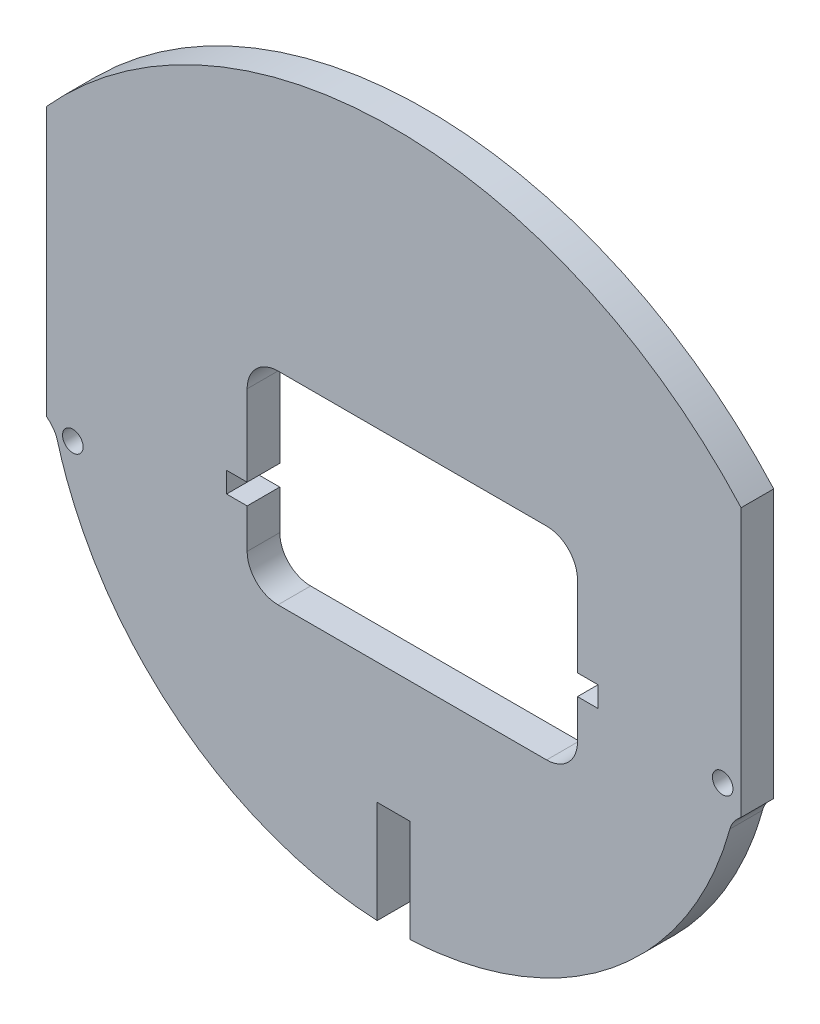
SolidWorks part; units mm, degrees
ref_plane "Front Plane" through (0, 0, 0) normal (0, 0, 1) x (1, 0, 0)
ref_plane "Top Plane" through (0, 0, 0) normal (0, 1, 0) x (1, 0, 0)
ref_plane "Right Plane" through (0, 0, 0) normal (1, 0, 0) x (0, 0, -1)
sketch "Sketch1" plane through (0, 0, 299.79) normal (0, 0, 1) x (1, 0, 0)
  line L4 (33.8, -7.3668) -> (33.8, 18.7258)
  line L5 (-33.8, 18.7232) -> (-33.8, -7.3668)
  line L6 (33.8, -7.3668) -> (33.8, 18.7258)
  line L7 (-33.8, 18.7232) -> (-33.8, -7.3668)
  arc A2 (33.8, 18.7258) -> (-33.8, 18.7232) centre (0.0012, -11.6296) ccw
  arc A3 (33.8, 18.7258) -> (-33.8, 18.7232) centre (0.0012, -11.6296) ccw
  spline S8 degree 3 poles (-1016.2927, 2781.193) (-581.3061, 1300.0591) (-161.7758, -90.3852) (11.2723, -31.8769) (11.7093, -31.7192) (12.5722, -31.3883) (13.8533, -30.8679) (16.7482, -29.4839) (19.0662, -28.003) (20.9048, -26.6015) (21.2687, -26.3121) (21.9818, -25.721) (22.3313, -25.4192) (23.3593, -24.4955) (25.3334, -22.5755) (27.0578, -20.4334) (28.6095, -18.1378) (29.099, -17.3449) (30.0051, -15.7345) (30.4243, -14.9144) (73.6573, 78.615) (-299.6884, 354.0447) (-2573.4248, 1463.866) knots -12.045008 -12.045008 -12.045008 -12.045008 0.25 0.25 0.28125 0.28125 0.3125 0.375 0.5 0.5 0.53125 0.53125 0.5625 0.5625 0.625 0.75 0.75 0.8125 0.8125 0.875 0.875 7.815594 7.815594 7.815594 7.815594 only from (0, -33.7996) to (32.7115, -8.8898)
  spline S9 degree 3 poles (3012.7008, -332.9993) (194.5659, -142.2921) (21.2536, -24.2042) (45.0624, 8.2078) (207.3281, -123.8641) (-2059.6696, 2140.7862) knots -30.844141 -30.844141 -30.844141 -30.844141 0.5 0.5 32.000269 32.000269 32.000269 32.000269 only from (32.7115, -8.8898) to (33.8, -7.3668)
  spline S10 degree 3 poles (1931.9323, 2258.2217) (-186.0941, -116.3959) (-47.7859, 6.5702) (-33.3262, -7.7914) (-33.2211, -7.9122) (-33.0345, -8.1665) (-32.9521, -8.3007) (-26.9906, -20.3777) (-108.782, -90.3547) (-1945.2248, 2299.9192) knots -31.496025 -31.496025 -31.496025 -31.496025 0.25 0.25 0.5 0.5 0.75 0.75 21.739069 21.739069 21.739069 21.739069 only from (-33.8, -7.3668) to (-32.7115, -8.8898)
  spline S11 degree 3 poles (2544.6593, 1514.4209) (266.9927, 341.713) (-71.9551, 75.0102) (-30.0469, -15.7324) (-29.1497, -17.3351) (-27.8537, -19.2568) (-27.5859, -19.6367) (-27.0375, -20.381) (-26.1942, -21.4772) (-25.2894, -22.5133) (-23.4001, -24.5077) (-22.0369, -25.736) (-20.1986, -27.1404) (-19.8234, -27.4151) (-18.307, -28.4773) (-17.131, -29.1958) (-14.2997, -30.6962) (-12.6159, -31.4206) (-9.9927, -32.3105) (-9.0996, -32.5737) (-7.3094, -33.0214) (-6.4087, -33.2074) (264.603, -77.6051) (1022.8864, 3211.8785) (666.5513, -1110.289) knots -6.570571 -6.570571 -6.570571 -6.570571 0.125 0.125 0.25 0.25 0.28125 0.28125 0.3125 0.375 0.375 0.5 0.5 0.53125 0.53125 0.625 0.625 0.75 0.75 0.8125 0.8125 0.875 0.875 19.504434 19.504434 19.504434 19.504434 only from (-32.7115, -8.8898) to (0, -33.7996)
  spline S12 degree 3 poles (0, -33.7996) (3.712, -33.7995) (7.3238, -33.2119) (11.2723, -31.8769) (11.7093, -31.7192) (12.5722, -31.3883) (13.8533, -30.8679) (16.7482, -29.4839) (19.0662, -28.003) (20.9048, -26.6015) (21.2687, -26.3121) (21.9818, -25.721) (22.3313, -25.4192) (23.3593, -24.4955) (25.3334, -22.5755) (27.0578, -20.4334) (28.6095, -18.1378) (29.099, -17.3449) (30.0051, -15.7345) (30.4243, -14.9144) (31.5818, -12.4103) (32.2185, -10.6815) (32.7115, -8.8898) knots 0 0 0 0 0.25 0.25 0.28125 0.28125 0.3125 0.375 0.5 0.5 0.53125 0.53125 0.5625 0.5625 0.625 0.75 0.75 0.8125 0.8125 0.875 0.875 1 1 1 1
  spline S13 degree 3 poles (32.7115, -8.8898) (32.7967, -8.5801) (32.939, -8.2963) (33.3179, -7.7806) (33.5452, -7.5601) (33.8, -7.3668) knots 0 0 0 0 0.5 0.5 1 1 1 1
  spline S14 degree 3 poles (-33.8, -7.3668) (-33.6728, -7.4633) (-33.5521, -7.567) (-33.3262, -7.7914) (-33.2211, -7.9122) (-33.0345, -8.1665) (-32.9521, -8.3007) (-32.8117, -8.585) (-32.754, -8.7354) (-32.7115, -8.8898) knots 0 0 0 0 0.25 0.25 0.5 0.5 0.75 0.75 1 1 1 1
  spline S15 degree 3 poles (-32.7115, -8.8898) (-32.2185, -10.6814) (-31.583, -12.4063) (-30.0469, -15.7324) (-29.1497, -17.3351) (-27.8537, -19.2568) (-27.5859, -19.6367) (-27.0375, -20.381) (-26.1942, -21.4772) (-25.2894, -22.5133) (-23.4001, -24.5077) (-22.0369, -25.736) (-20.1986, -27.1404) (-19.8234, -27.4151) (-18.307, -28.4773) (-17.131, -29.1958) (-14.2997, -30.6962) (-12.6159, -31.4206) (-9.9927, -32.3105) (-9.0996, -32.5737) (-7.3094, -33.0214) (-4.6073, -33.5794) (-1.8558, -33.7996) (0, -33.7996) knots 0 0 0 0 0.125 0.125 0.25 0.25 0.28125 0.28125 0.3125 0.375 0.375 0.5 0.5 0.53125 0.53125 0.625 0.625 0.75 0.75 0.8125 0.8125 0.875 1 1 1 1
  dimension "D1" = 1
extrude "Boss-Extrude1" add sketch "Sketch1" against normal blind 3.175
sketch "Sketch2" plane through (0, 0, 296.615) normal (0, 0, -1) x (-1, 0, 0)
  line L4 (-23.8, 14.6162) -> (-23.8, -4.2553)
  line L5 (23.8, -4.2556) -> (23.8, 14.6141)
  line L6 (-23.8, 14.6162) -> (-23.8, -4.2553)
  line L7 (23.8, -4.2556) -> (23.8, 14.6141)
  arc A2 (23.8, 14.6141) -> (-23.8, 14.6162) centre (-0.0012, -11.6296) ccw
  arc A3 (23.8, 14.6141) -> (-23.8, 14.6162) centre (-0.0012, -11.6296) ccw
  circle A4 centre (-32.0093, -5.359) radius 1
  circle A5 centre (-32.0093, -5.359) radius 1
  circle A6 centre (31.2161, -8.1644) radius 1
  circle A7 centre (31.2161, -8.1644) radius 1
  spline S8 degree 3 poles (2588.6585, 1461.9481) (237.4059, 279.2145) (-53.6805, 59.1859) (-21.188, -11.0621) (-20.5557, -12.1928) (-19.4591, -13.8197) (-19.0712, -14.346) (-18.2586, -15.3576) (-17.8329, -15.8444) (-16.4995, -17.2501) (-15.5379, -18.1162) (-13.9825, -19.3052) (-13.4457, -19.6815) (-12.3523, -20.3817) (-11.7936, -20.7074) (-10.0819, -21.6131) (-8.8941, -22.123) (-7.0446, -22.7511) (-6.4151, -22.9369) (-5.1531, -23.2528) (-4.5182, -23.3839) (146.6784, -48.1096) (514.4313, 1408.8154) (23.9713, -2988.3593) knots -7.237863 -7.237863 -7.237863 -7.237863 0.125 0.125 0.25 0.25 0.3125 0.3125 0.375 0.375 0.5 0.5 0.5625 0.5625 0.625 0.625 0.75 0.75 0.8125 0.8125 0.875 0.875 15.604534 15.604534 15.604534 15.604534 only from (-23.0698, -6.2368) to (0, -23.7996)
  spline S9 degree 3 poles (-2928.51, -741.6682) (-53.0027, 117.8572) (1751.1569, 582.5973) (-2739.2696, -1272.1811) knots -147.93974 -147.93974 -147.93974 -147.93974 118.763391 118.763391 118.763391 118.763391 only from (-23.8, -4.2553) to (-23.0698, -6.2368)
  spline S10 degree 3 poles (2745.3916, -1259.0395) (-4951.2339, 1886.1992) (6692.7962, -2096.1576) (1214.6192, 231.5182) knots -110.892959 -110.892959 -110.892959 -110.892959 300.787119 300.787119 300.787119 300.787119 only from (23.0698, -6.2368) to (23.8, -4.2556)
  spline S11 degree 3 poles (-870.5324, 810.2078) (-1093.2425, 3555.5343) (-224.363, -101.0834) (8.2579, -22.3397) (8.8686, -22.106) (10.0606, -21.5942) (10.6439, -21.3154) (12.3557, -20.4105) (13.4453, -19.7143) (15.0007, -18.5277) (15.506, -18.1092) (16.4726, -17.2408) (16.9364, -16.7892) (18.2706, -15.3838) (19.0816, -14.3772) (20.1754, -12.7583) (20.5206, -12.1991) (21.1595, -11.0633) (21.4548, -10.4848) (54.7957, 61.5445) (-261.3264, 286.2476) (-2618.6825, 1406.8637) knots -23.18789 -23.18789 -23.18789 -23.18789 0.25 0.25 0.3125 0.3125 0.375 0.375 0.5 0.5 0.5625 0.5625 0.625 0.625 0.75 0.75 0.8125 0.8125 0.875 0.875 8.46157 8.46157 8.46157 8.46157 only from (0, -23.7996) to (23.0698, -6.2368)
  spline S12 degree 3 poles (-23.0698, -6.2368) (-22.7221, -7.5005) (-22.2728, -8.7167) (-21.188, -11.0621) (-20.5557, -12.1928) (-19.4591, -13.8197) (-19.0712, -14.346) (-18.2586, -15.3576) (-17.8329, -15.8444) (-16.4995, -17.2501) (-15.5379, -18.1162) (-13.9825, -19.3052) (-13.4457, -19.6815) (-12.3523, -20.3817) (-11.7936, -20.7074) (-10.0819, -21.6131) (-8.8941, -22.123) (-7.0446, -22.7511) (-6.4151, -22.9369) (-5.1531, -23.2528) (-4.5182, -23.3839) (-2.6016, -23.6973) (-1.3083, -23.7996) (0, -23.7996) knots 0 0 0 0 0.125 0.125 0.25 0.25 0.3125 0.3125 0.375 0.375 0.5 0.5 0.5625 0.5625 0.625 0.625 0.75 0.75 0.8125 0.8125 0.875 0.875 1 1 1 1
  spline S13 degree 3 poles (-23.8, -4.2553) (-23.5007, -4.8952) (-23.2572, -5.5557) (-23.0698, -6.2368) knots 0 0 0 0 1 1 1 1
  spline S14 degree 3 poles (23.0698, -6.2368) (23.2572, -5.5558) (23.5008, -4.8954) (23.8, -4.2556) knots 0 0 0 0 1 1 1 1
  spline S15 degree 3 poles (0, -23.7996) (2.6175, -23.7995) (5.1646, -23.3868) (8.2579, -22.3397) (8.8686, -22.106) (10.0606, -21.5942) (10.6439, -21.3154) (12.3557, -20.4105) (13.4453, -19.7143) (15.0007, -18.5277) (15.506, -18.1092) (16.4726, -17.2408) (16.9364, -16.7892) (18.2706, -15.3838) (19.0816, -14.3772) (20.1754, -12.7583) (20.5206, -12.1991) (21.1595, -11.0633) (21.4548, -10.4848) (22.2721, -8.7192) (22.7221, -7.5005) (23.0698, -6.2368) knots 0 0 0 0 0.25 0.25 0.3125 0.3125 0.375 0.375 0.5 0.5 0.5625 0.5625 0.625 0.625 0.75 0.75 0.8125 0.8125 0.875 0.875 1 1 1 1
  dimension "D1" = 10
  dimension "D2" = 0
  dimension "D3" = 0
extrude "Cut-Extrude1" cut sketch "Sketch2" against normal blind 3.175 contours A7 | A5
sketch "Sketch3" plane through (0, 0, 299.79) normal (0, 0, 1) x (1, 0, 0)
  line L0 (-1.6006, -34.7702) -> (1.5744, -34.7702) construction
  line L1 (-1.6006, -23.7996) -> (-1.6006, -34.7702) construction
  line L2 (-1.6006, -23.7996) -> (1.5744, -23.7996) construction
  line L3 (1.5744, -34.7702) -> (1.5744, -23.7996) construction
  line L4 (-1.6006, -34.7702) -> (1.5744, -34.7702)
  line L5 (-1.6006, -23.7996) -> (-1.6006, -34.7702)
  line L6 (-1.6006, -23.7996) -> (1.5744, -23.7996)
  line L7 (1.5744, -34.7702) -> (1.5744, -23.7996)
extrude "Cut-Extrude2" cut sketch "Sketch3" against normal through all
sketch "Sketch4" plane through (0, 0, 296.615) normal (0, 0, -1) x (-1, 0, 0)
  line L4 (11.2577, 7.7172) -> (-14.8786, 7.7172)
  line L5 (11.2577, 7.7172) -> (-14.8786, 7.7172)
  line L6 (-17.8786, 4.7172) -> (-17.8786, -8.9843)
  line L7 (-17.8786, 4.7172) -> (-17.8786, -8.9843)
  line L32 (-14.8786, -11.9843) -> (11.2577, -11.9843)
  line L33 (-14.8786, -11.9843) -> (11.2577, -11.9843)
  line L34 (14.2577, -8.9843) -> (14.2577, 4.7172)
  line L35 (14.2577, -8.9843) -> (14.2577, 4.7172)
  line L108 (-19.8786, -3.1502) -> (-19.8786, -5.1502) construction
  line L109 (-19.8786, -5.1502) -> (-17.8786, -5.1502) construction
  line L110 (-17.8786, -5.1502) -> (-17.8786, -3.1502) construction
  line L111 (-17.8786, -3.1502) -> (-19.8786, -3.1502) construction
  line L115 (14.2577, -3.1502) -> (16.2577, -3.1502) construction
  line L116 (14.2577, -5.1502) -> (14.2577, -3.1502) construction
  line L117 (16.2577, -5.1502) -> (14.2577, -5.1502) construction
  line L123 (-19.8786, -3.1502) -> (-19.8786, -5.1502)
  line L124 (-19.8786, -5.1502) -> (-17.8786, -5.1502)
  line L125 (-17.8786, -5.1502) -> (-17.8786, -3.1502)
  line L126 (-17.8786, -3.1502) -> (-19.8786, -3.1502)
  line L127 (16.2577, -3.1502) -> (16.2577, -5.1502)
  line L130 (14.2577, -3.1502) -> (16.2577, -3.1502)
  line L131 (14.2577, -5.1502) -> (14.2577, -3.1502)
  line L132 (16.2577, -5.1502) -> (14.2577, -5.1502)
  arc A28 (-14.8786, 7.7172) -> (-17.8786, 4.7172) centre (-14.8786, 4.7172) ccw
  arc A29 (-14.8786, 7.7172) -> (-17.8786, 4.7172) centre (-14.8786, 4.7172) ccw
  arc A30 (-17.8786, -8.9843) -> (-14.8786, -11.9843) centre (-14.8786, -8.9843) ccw
  arc A31 (-17.8786, -8.9843) -> (-14.8786, -11.9843) centre (-14.8786, -8.9843) ccw
  arc A32 (11.2577, -11.9843) -> (14.2577, -8.9843) centre (11.2577, -8.9843) ccw
  arc A33 (11.2577, -11.9843) -> (14.2577, -8.9843) centre (11.2577, -8.9843) ccw
  arc A34 (14.2577, 4.7172) -> (11.2577, 7.7172) centre (11.2577, 4.7172) ccw
  arc A35 (14.2577, 4.7172) -> (11.2577, 7.7172) centre (11.2577, 4.7172) ccw
  dimension "D1" = 0
extrude "Cut-Extrude3" cut sketch "Sketch4" against normal through all contours L35 A35 L5 A29 L7 A31 L33 A33 | L132 L127 L130 L35 | L126 L123 L124 L125
